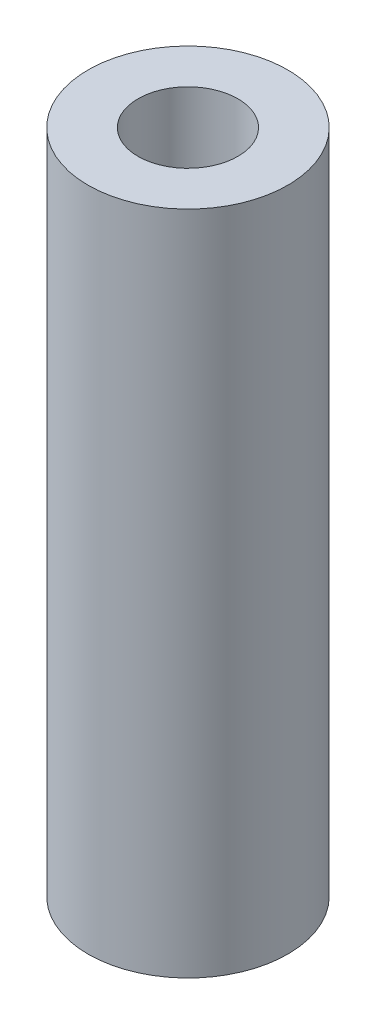
SolidWorks part; units mm, degrees
ref_plane "Front Plane" through (0, 0, 0) normal (0, 0, 1) x (1, 0, 0)
ref_plane "Top Plane" through (0, 0, 0) normal (0, 1, 0) x (1, 0, 0)
ref_plane "Right Plane" through (0, 0, 0) normal (1, 0, 0) x (0, 0, -1)
sketch "Sketch1" plane through (0, 0, 0) normal (0, 1, 0) x (1, 0, 0)
  circle A0 centre (0, 0) radius 3
  circle A1 centre (0, 0) radius 1.5
  dimension "D1" = 6
  dimension "D2" = 3
extrude "Boss-Extrude1" add sketch "Sketch1" along normal blind 20
